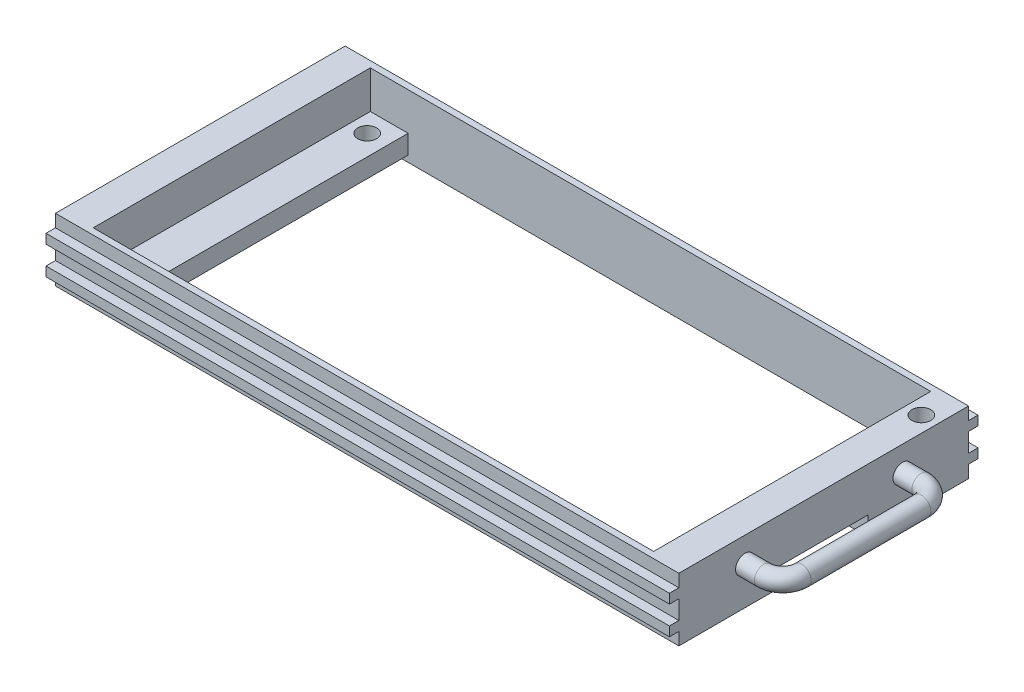
SolidWorks part; units mm, degrees
ref_plane "Front Plane" through (0, 0, 0) normal (0, 0, 1) x (1, 0, 0)
ref_plane "Top Plane" through (0, 0, 0) normal (0, 1, 0) x (1, 0, 0)
ref_plane "Right Plane" through (0, 0, 0) normal (1, 0, 0) x (0, 0, -1)
sketch "Sketch1" plane through (0, 0, 0) normal (0, 1, 0) x (1, 0, 0)
  line L1 (-49.5, -23) -> (49.5, -23)
  line L2 (-49.5, -23) -> (-49.5, 23)
  line L3 (-49.5, 23) -> (49.5, 23)
  line L4 (49.5, -23) -> (49.5, 23)
  line L5 (-49.5, -23) -> (49.5, 23) construction
  line L6 (-49.5, 23) -> (49.5, -23) construction
  line L7 (-44.5, -22) -> (44.5, -22)
  line L8 (-44.5, -22) -> (-44.5, 22)
  line L9 (-44.5, 22) -> (44.5, 22)
  line L10 (44.5, -22) -> (44.5, 22)
  line L11 (-44.5, -22) -> (44.5, 22) construction
  line L12 (-44.5, 22) -> (44.5, -22) construction
  point P0 (0, 0)
  point P6 (0, 0)
  dimension "D1" = 44
  dimension "D2" = 89
  dimension "D3" = 46
  dimension "D4" = 99
extrude "Boss-Extrude1" add sketch "Sketch1" along normal blind 10
sketch "Sketch2" plane through (0, 0, 23) normal (0, 0, 1) x (1, 0, 0)
  line L0 (49.5, 10) -> (49.5, 0) construction
  line L1 (-49.5, 2) -> (49.5, 2)
  line L2 (-49.5, 2) -> (-49.5, 3.5)
  line L3 (-49.5, 3.5) -> (49.5, 3.5)
  line L4 (49.5, 2) -> (49.5, 3.5)
  line L5 (-49.5, 0) -> (49.5, 0) construction
  line L6 (-49.5, 6.5) -> (49.5, 6.5)
  line L7 (49.5, 6.5) -> (49.5, 8)
  line L8 (-49.5, 6.5) -> (-49.5, 8)
  line L9 (-49.5, 8) -> (49.5, 8)
  dimension "D1" = 1.5
  dimension "D2" = 2
  dimension "D3" = 1.5
  dimension "D4" = 3
  dimension "D5" = 99
extrude "Boss-Extrude2" add sketch "Sketch2" along normal blind 1.5
mirror "Mirror1" about plane through (0, 0, 0) normal (0, 0, 1) of "Boss-Extrude2"
sketch "Sketch4" plane through (0, 0, 0) normal (0, 1, 0) x (1, 0, 0)
  line L0 (-44.5, -22) -> (44.5, -22) construction
  line L1 (-44.5, 22) -> (-38.5, 22)
  line L2 (-44.5, 22) -> (-44.5, -22)
  line L3 (-44.5, -22) -> (-38.5, -22)
  line L4 (-38.5, 22) -> (-38.5, -22)
  dimension "D1" = 6
extrude "Boss-Extrude3" add sketch "Sketch4" along normal blind 4
mirror "Mirror2" about plane through (0, 0, 0) normal (1, 0, 0) of "Boss-Extrude3"
sketch "Sketch5" plane through (0, 4, 0) normal (0, 1, 0) x (1, 0, 0)
  line L0 (-44.5, 22) -> (-44.5, -22) construction
  line L1 (-38.5, 0) -> (-49.5, 0) construction
  line L2 (-38.5, -22) -> (-38.5, 22) construction
  line L3 (-49.5, 23) -> (-49.5, -23) construction
  circle A0 centre (-41.75, 18.75) radius 1.5
  circle A1 centre (-41.75, -18.75) radius 1.5
  dimension "D1" = 3
  dimension "D2" = 2.75
  dimension "D3" = 37.5
extrude "Cut-Extrude1" cut sketch "Sketch5" against normal up to surface (4 mm away) up to face at (0, 0, 0)
mirror "Mirror3" about plane through (0, 0, 0) normal (1, 0, 0) of "Cut-Extrude1"
sketch "Sketch6" plane through (0, 0, 0) normal (0, -1, 0) x (1, 0, 0)
  line L0 (38.5, -22) -> (-38.5, -22) construction
  line L1 (-38.5, 22) -> (-44.5, 22)
  line L2 (-38.5, 22) -> (-38.5, -22)
  line L3 (-38.5, -22) -> (-44.5, -22)
  line L4 (-44.5, 22) -> (-44.5, -22)
  line L5 (0, -55) -> (0, 55) construction
  line L6 (44.5, 22) -> (44.5, -22)
  line L7 (38.5, -22) -> (44.5, -22)
  line L8 (38.5, 22) -> (38.5, -22)
  line L9 (38.5, 22) -> (44.5, 22)
  dimension "D1" = 6
extrude "Cut-Extrude2" cut sketch "Sketch6" against normal blind 1
sketch "Sketch7" plane through (49.5, 0, 0) normal (1, 0, 0) x (0, 0, -1)
  line L5 (-23, 0) -> (23, 0) construction
  line L6 (-7, 0) -> (7, 0)
  line L9 (-7, 0) -> (-7, 3)
  line L10 (0, 10) -> (0, 12.6098) construction
  line L11 (-23, 10) -> (23, 10) construction
  line L12 (-7, 3) -> (7, 3)
  line L13 (7, 0) -> (7, 3)
  point P6 (0, 3)
  dimension "D1" = 14
  dimension "D2" = 3
extrude "Cut-Extrude3" cut sketch "Sketch7" against normal up to surface (11 mm away) up to face at (38.5, 2.5, 0)
ref_plane "Plane1" through (0, 6, 0) normal (0, 1, 0) x (1, 0, 0)
sketch "Sketch8" plane through (49.5, 0, 0) normal (1, 0, 0) x (0, 0, -1)
  line L0 (-12.5, 6) -> (12.5, 6) construction
  line L1 (-23, 10) -> (23, 10) construction
  circle A0 centre (12.5, 6) radius 2
  circle A1 centre (-12.5, 6) radius 2
  point P4 (0, 6)
  dimension "D1" = 4
  dimension "D2" = 4
  dimension "D3" = 25
  dimension "D4" = 4
sketch "Sketch9" plane through (0, 6, 0) normal (0, 1, 0) x (1, 0, 0)
  line L0 (49.5, 12.5) -> (52.5, 12.5)
  line L1 (49.5, -12.5) -> (49.5, 12.5) construction
  line L2 (55.5, 9.5) -> (55.5, -9.5)
  line L3 (52.5, -12.5) -> (49.5, -12.5)
  line L4 (49.5, -14.5) -> (49.5, -10.5) construction
  arc A0 (55.5, -9.5) -> (52.5, -12.5) centre (52.5, -9.5) cw
  arc A1 (52.5, 12.5) -> (55.5, 9.5) centre (52.5, 9.5) cw
  dimension "D1" = 3
  dimension "D2" = 6
sweep "Sweep3" add path "Sketch9" circular profile diameter 3 parameters "D3"=3
sketch "Sketch23" plane through (0, 10, 0) normal (0, 1, 0) x (1, 0, 0)
  line L0 (44.5, 22) -> (44.5, -22) construction
  line L1 (49.5, 23) -> (-49.5, 23) construction
  circle A0 centre (47, 18) radius 1.5
  dimension "D1" = 3
  dimension "D2" = 2.5
  dimension "D3" = 5
extrude "Cut-Extrude4" cut sketch "Sketch23" against normal up to surface (10 mm away) up to face at (15.6667, 0, 0)
